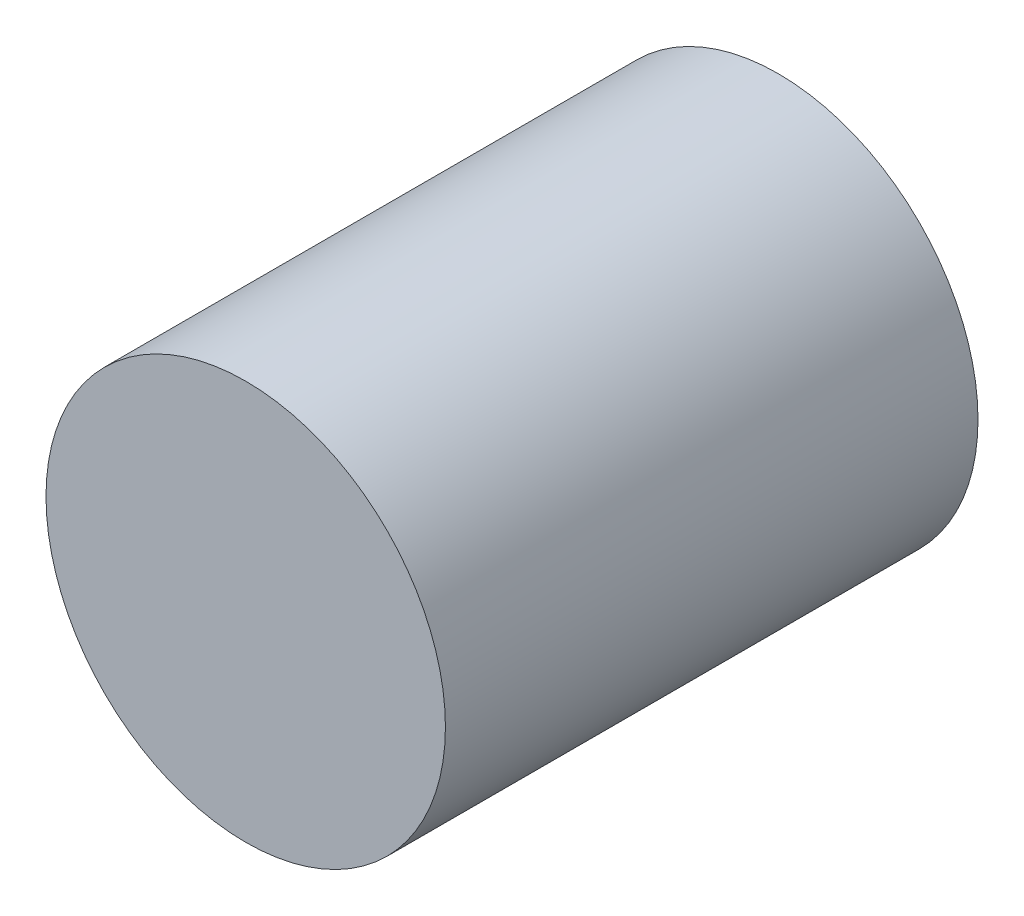
SolidWorks part; units mm, degrees
ref_plane "Front Plane" through (0, 0, 0) normal (0, 0, 1) x (1, 0, 0)
ref_plane "Top Plane" through (0, 0, 0) normal (0, 1, 0) x (1, 0, 0)
ref_plane "Right Plane" through (0, 0, 0) normal (1, 0, 0) x (0, 0, -1)
sketch "Sketch1" plane through (0, 0, 0) normal (0, 0, 1) x (1, 0, 0)
  circle A0 centre (0, 0) radius 22.5
  dimension "D1" = 45
extrude "Boss-Extrude1" add sketch "Sketch1" along normal mid plane 60
